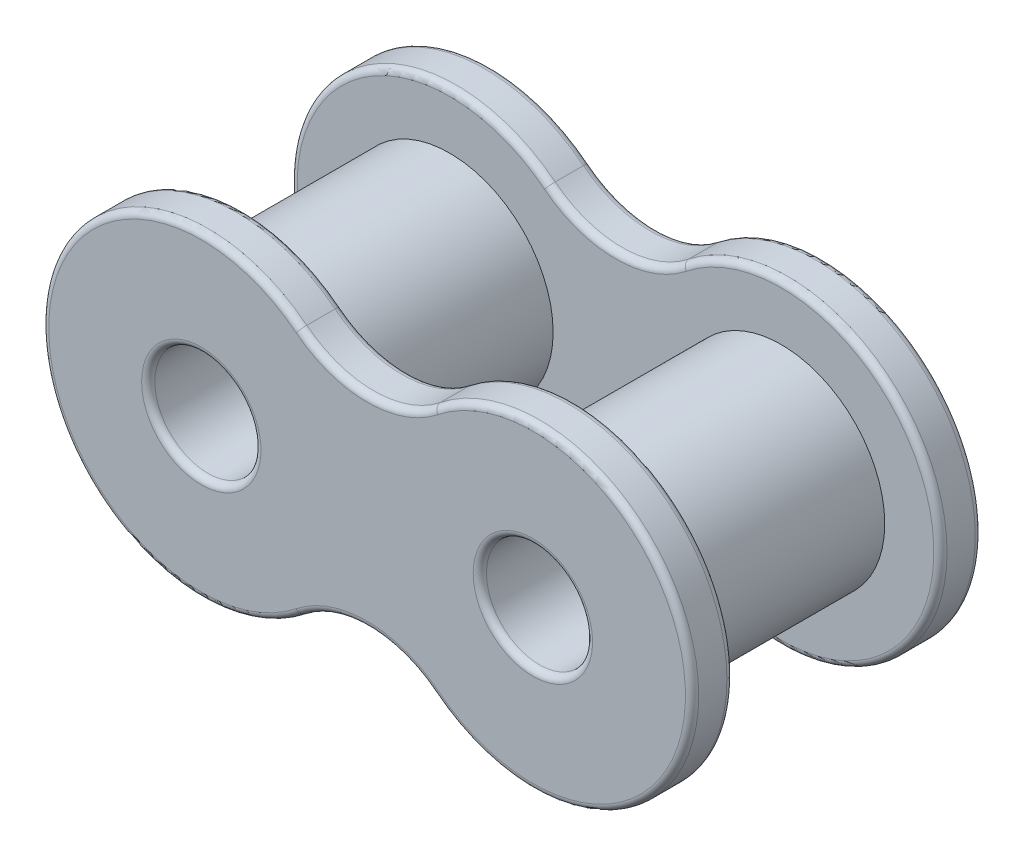
SolidWorks part; units mm, degrees
ref_plane "前基準面" through (0, 0, 0) normal (0, 0, 1) x (1, 0, 0)
ref_plane "上基準面" through (0, 0, 0) normal (0, 1, 0) x (1, 0, 0)
ref_plane "右基準面" through (0, 0, 0) normal (1, 0, 0) x (0, 0, -1)
sketch "草圖1" plane through (0, 0, 0) normal (0, 0, 1) x (1, 0, 0)
  line L0 (0, 6.4262) -> (0, -9.3857) construction
  line L1 (-11.2033, 0) -> (19.0676, 0) construction
  circle A0 centre (-6.35, 0) radius 2.032
  arc A1 (-2.5601, 4.7747) -> (-2.5601, -4.7747) centre (-6.35, 0) ccw
  circle A2 centre (6.35, 0) radius 2.032
  arc A3 (2.5601, 4.7747) -> (2.5601, -4.7747) centre (6.35, 0) cw
  arc A4 (-2.5601, 4.7747) -> (2.5601, 4.7747) centre (0, 8) ccw
  arc A5 (-2.5601, -4.7747) -> (2.5601, -4.7747) centre (0, -8) cw
  dimension "D1" = 4.064
  dimension "D2" = 12.192
  dimension "D3" = 6.35
  dimension "D4" = 8
extrude "填料-伸長1" add sketch "草圖1" along normal blind 1.5875
fillet "圓角1" radius 0.254 12 edges at (4.318, 0, 1.5875) (12.446, 0, 1.5875) (0, -3.8822, 1.5875) (-12.446, 0, 1.5875) (0, 3.8822, 1.5875) (-4.318, 0, 1.5875) (4.318, 0, 0) (-4.318, 0, 0) (-12.446, 0, 0) (0, -3.8822, 0) (12.446, 0, 0) (0, 3.8822, 0)
sketch "草圖2" plane through (0, 0, 1.5875) normal (0, 0, 1) x (1, 0, 0)
  circle A0 centre (-6.35, 0) radius 2.032 construction
  circle A1 centre (-6.35, 0) radius 2.032
  circle A2 centre (-6.35, 0) radius 3.9624
  dimension "D1" = 7.9248
extrude "填料-伸長2" add sketch "草圖2" along normal blind 7.9248
mirror "鏡射1" about plane through (0, 0, 0) normal (1, 0, 0) of "填料-伸長2"
ref_plane "平面1" through (0, 0, 5.5499) normal (0, 0, 1) x (1, 0, 0)
mirror "鏡射2" about plane through (0, 0, 5.5499) normal (0, 0, 1) of "填料-伸長1"
fillet "圓角2" radius 0.254 10 edges at (12.446, 0, 9.5123) (0, -3.8822, 9.5123) (-12.446, 0, 9.5123) (12.446, 0, 11.0998) (0, -3.8822, 11.0998) (-12.446, 0, 11.0998) (0, 3.8822, 11.0998) (4.318, 0, 11.0998) (-4.318, 0, 11.0998) (0, 3.8822, 9.5123)
